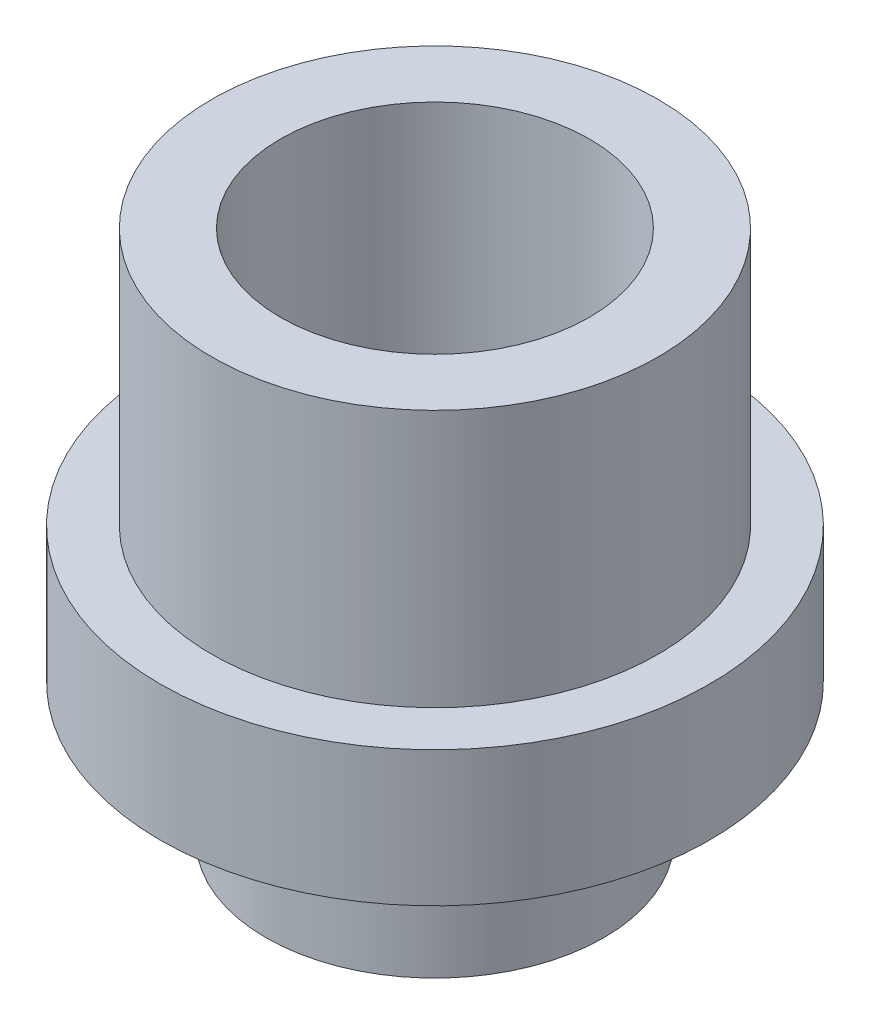
SolidWorks part; units mm, degrees
ref_plane "Front Plane" through (0, 0, 0) normal (0, 0, 1) x (1, 0, 0)
ref_plane "Top Plane" through (0, 0, 0) normal (0, 1, 0) x (1, 0, 0)
ref_plane "Right Plane" through (0, 0, 0) normal (1, 0, 0) x (0, 0, -1)
sketch "Sketch1" plane through (0, 0, 0) normal (0, 1, 0) x (1, 0, 0)
  circle A0 centre (0, 0) radius 20.32
  circle A1 centre (0, 0) radius 4.0957
  dimension "D1" = 40.64
  dimension "D2" = 8.1915
extrude "Boss-Extrude1" add sketch "Sketch1" along normal blind 10
sketch "Sketch2" plane through (0, 10, 0) normal (0, 1, 0) x (1, 0, 0)
  circle A0 centre (0, 0) radius 16.51
  circle A1 centre (0, 0) radius 11.43
  dimension "D1" = 33.02
  dimension "D2" = 22.86
extrude "Boss-Extrude2" add sketch "Sketch2" along normal blind 19.05
sketch "Sketch3" plane through (0, 0, 0) normal (0, -1, 0) x (-1, 0, 0)
  circle A0 centre (0, 0) radius 12.5
  circle A1 centre (0, 0) radius 4.0957
  dimension "D1" = 25
extrude "Boss-Extrude3" add sketch "Sketch3" along normal blind 10.16
